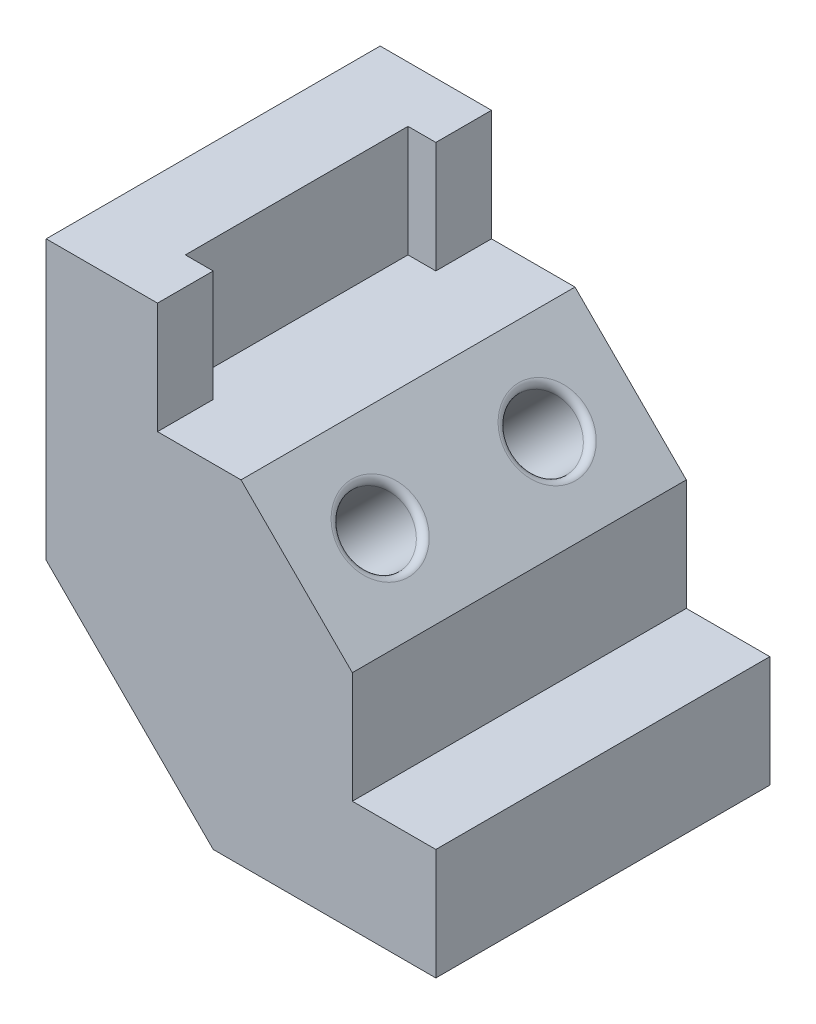
SolidWorks part; units mm, degrees
ref_plane "Front Plane" through (0, 0, 0) normal (0, 0, 1) x (1, 0, 0)
ref_plane "Top Plane" through (0, 0, 0) normal (0, 1, 0) x (1, 0, 0)
ref_plane "Right Plane" through (0, 0, 0) normal (1, 0, 0) x (0, 0, -1)
sketch "Sketch2" plane through (0, 0, 0) normal (0, 0, 1) x (1, 0, 0)
  line L0 (0, 48.3513) -> (0, -15.1487)
  line L1 (0, -15.1487) -> (38.1, -53.2487)
  line L2 (38.1, -53.2487) -> (88.9, -53.2487)
  line L3 (88.9, -53.2487) -> (88.9, -27.8487)
  line L4 (88.9, -27.8487) -> (69.85, -27.8487)
  line L5 (69.85, -27.8487) -> (69.85, -2.4487)
  line L6 (69.85, -2.4487) -> (44.45, 22.9513)
  line L7 (44.45, 22.9513) -> (25.4, 22.9513)
  line L8 (25.4, 22.9513) -> (25.4, 48.3513)
  line L9 (25.4, 48.3513) -> (0, 48.3513)
  dimension "D1" = 101.6
  dimension "D2" = 25.4
  dimension "D3" = 44.45
  dimension "D4" = 76.2
  dimension "D5" = 25.4
  dimension "D6" = 50.8
  dimension "D7" = 38.1
  dimension "D8" = 88.9
  dimension "D9" = 45
extrude "Boss-Extrude2" add sketch "Sketch2" against normal blind 76.2
sketch "Sketch3" plane through (0, 48.3513, 0) normal (0, 1, 0) x (1, 0, 0)
  line L2 (19.05, 76.2) -> (19.05, 0)
  line L3 (19.05, 63.5) -> (19.05, 12.7)
  line L5 (25.4, 63.5) -> (0, 63.5)
  line L6 (25.4, 63.5) -> (19.05, 63.5)
  line L7 (25.4, 63.5) -> (25.4, 12.7)
  line L8 (25.4, 12.7) -> (0, 12.7)
  line L9 (25.4, 12.7) -> (19.05, 12.7)
  dimension "D1" = 6.35
  dimension "D2" = 12.7
  dimension "D3" = 12.7
extrude "Cut-Extrude1" cut sketch "Sketch3" against normal up to surface (25.4 mm away) up to face at (34.925, 22.9513, -38.1)
sketch "Sketch4" plane through (33.7007, 33.7007, 0) normal (0.7071, 0.7071, 0) x (0, 0, -1)
  line L0 (76.2, -51.1229) -> (0, -51.1229) construction
  line L3 (38.1, 34.1895) -> (38.1, -101.1793)
  line L4 (76.2, 34.1895) -> (0, 34.1895) construction
  circle A0 centre (19.05, -33.1651) radius 7.62
  circle A1 centre (57.15, -33.1651) radius 7.62
  dimension "D1" = 15.24
  dimension "D2" = 15.24
  dimension "D3" = 17.9578
  dimension "D4" = 17.9578
  dimension "D5" = 38.1
extrude "Cut-Extrude2" cut sketch "Sketch4" against normal blind 53.34 contours A0 | A1
fillet "Fillet2" radius 1.524 2 edges at (51.7638, 15.6376, -57.15) (51.7638, 15.6376, -19.05)
